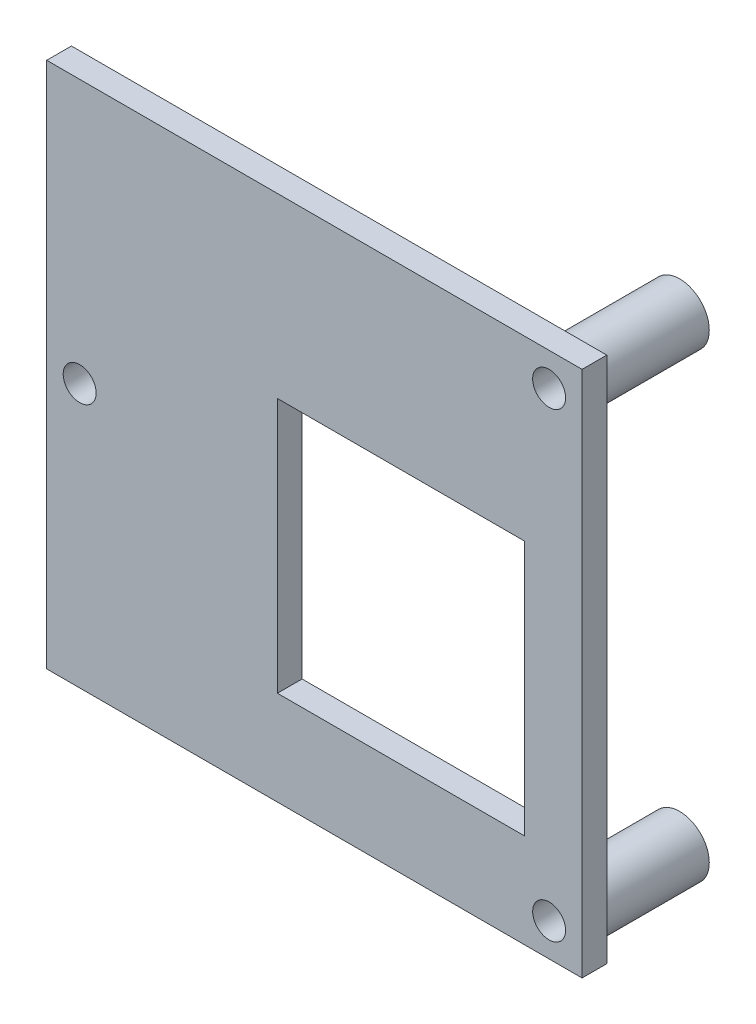
SolidWorks part; units mm, degrees
ref_plane "Front Plane" through (0, 0, 0) normal (0, 0, 1) x (1, 0, 0)
ref_plane "Top Plane" through (0, 0, 0) normal (0, 1, 0) x (1, 0, 0)
ref_plane "Right Plane" through (0, 0, 0) normal (1, 0, 0) x (0, 0, -1)
sketch "Sketch1" plane through (0, -0.0001, 1278.6214) normal (0, 0, 1) x (1, 0, 0)
  line L0 (-190.0462, 55.4549) -> (-190.0462, 119.4549) construction
  line L1 (-255.0462, 55.4549) -> (-190.0462, 55.4549) construction
  line L2 (-255.0462, 119.4549) -> (-255.0462, 55.4549) construction
  line L3 (-190.0462, 119.4549) -> (-255.0462, 119.4549) construction
  line L4 (-190.0462, 55.4549) -> (-190.0462, 119.4549)
  line L5 (-255.0462, 55.4549) -> (-190.0462, 55.4549)
  line L6 (-255.0462, 119.4549) -> (-255.0462, 55.4549)
  line L7 (-190.0462, 119.4549) -> (-255.0462, 119.4549)
extrude "Boss-Extrude1" add sketch "Sketch1" along normal blind 3
sketch "Sketch2" plane through (0, -0.0001, 1281.6214) normal (0, 0, -1) x (-1, 0, 0)
  line L0 (190.0462, 55.4549) -> (190.0462, 119.4549) construction
  line L1 (255.0462, 55.4549) -> (190.0462, 55.4549) construction
  line L2 (190.0462, 119.4549) -> (255.0462, 119.4549) construction
  line L3 (255.0462, 119.4549) -> (255.0462, 55.4549) construction
  point P0 (251.0462, 87.4549)
  point P1 (194.0462, 115.4549)
  point P2 (194.0462, 59.4549)
  point P3 (194.1824, 59.4549)
  point P4 (193.5639, 59.8664)
  dimension "D1" = 4
  dimension "D2" = 4
  dimension "D3" = 4
  dimension "D4" = 4
  dimension "D5" = 4
  dimension "D6" = 32
hole_wizard "Ø4.0mm Dowel Hole1" positions "Sketch2" profile "Sketch3" hole size "Ø4.0" standard "DIN" end condition up to next
sketch "Sketch3" plane through (-251.0462, 87.4548, 1281.6214) normal (1, 0, 0) x (0, -1, 0)
  line L0 (0, 0) -> (0, 3)
  line L1 (0, 3) -> (2, 3)
  line L2 (2, 3) -> (2, 0)
  line L5 (2, 0) -> (0, 0)
  line L11 (0, -6.35) -> (0, 107.95) construction
  dimension "Thru Hole Dia." = 4
  dimension "Thru Hole Depth" = 3
sketch "Sketch4" plane through (0, -0.0001, 1278.6214) normal (0, 0, -1) x (-1, 0, 0)
  circle A0 centre (194.0462, 115.4549) radius 3.6
  circle A1 centre (194.0462, 115.4549) radius 2 construction
  circle A2 centre (251.0462, 87.4549) radius 3.6
  circle A3 centre (251.0462, 87.4549) radius 2 construction
  circle A4 centre (194.0462, 59.4549) radius 3.6
  circle A5 centre (194.0462, 59.4549) radius 2 construction
  circle A6 centre (194.0462, 115.4549) radius 2
  circle A7 centre (194.0462, 59.4549) radius 2
  circle A8 centre (251.0462, 87.4549) radius 2
  dimension "D1" = 7.2
extrude "Boss-Extrude2" add sketch "Sketch4" along normal up to surface (12.8456 mm away)
sketch "Sketch5" plane through (0, -0.0001, 1281.6214) normal (0, 0, 1) x (1, 0, 0)
  line L0 (-197.0382, 68.8013) -> (-197.0382, 96.0013) construction
  line L1 (-227.0382, 97.9013) -> (-197.0382, 97.9013)
  line L2 (-227.0382, 97.9013) -> (-227.0382, 66.9013)
  line L3 (-227.0382, 66.9013) -> (-197.0382, 66.9013)
  line L4 (-197.0382, 97.9013) -> (-197.0382, 66.9013)
  line L5 (-227.0382, 96.0013) -> (-227.0382, 68.8013) construction
  line L7 (-222.2882, 66.9013) -> (-217.2882, 66.9013) construction
  line L8 (-217.2882, 97.9013) -> (-222.2882, 97.9013) construction
extrude "Cut-Extrude4" cut sketch "Sketch5" against normal up to next
